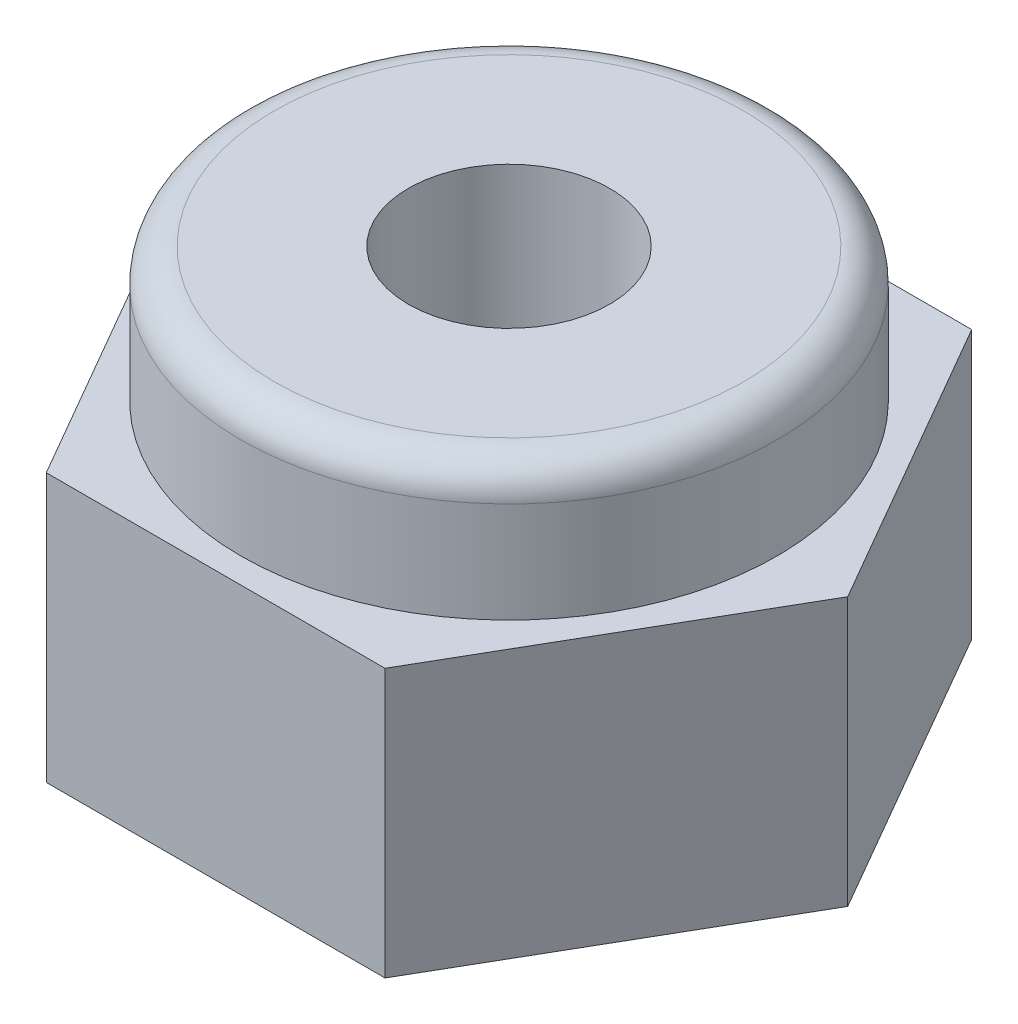
SolidWorks part; units mm, degrees
ref_plane "Front Plane" through (0, 0, 0) normal (0, 0, 1) x (1, 0, 0)
ref_plane "Top Plane" through (0, 0, 0) normal (0, 1, 0) x (1, 0, 0)
ref_plane "Right Plane" through (0, 0, 0) normal (1, 0, 0) x (0, 0, -1)
sketch "Sketch1" plane through (0, 0, 0) normal (0, 1, 0) x (1, 0, 0)
  line L1 (2.5259, 4.375) -> (-2.5259, 4.375)
  line L2 (-2.5259, 4.375) -> (-5.0518, 0)
  line L3 (-5.0518, 0) -> (-2.5259, -4.375)
  line L4 (-2.5259, -4.375) -> (2.5259, -4.375)
  line L5 (2.5259, -4.375) -> (5.0518, 0)
  line L6 (5.0518, 0) -> (2.5259, 4.375)
  circle A0 centre (0, 0) radius 4.375 construction
  circle A1 centre (0, 0) radius 1.5
  dimension "D2" = 3
  dimension "D1" = 8.75
extrude "Boss-Extrude1" add sketch "Sketch1" along normal blind 4
sketch "Sketch2" plane through (0, 4, 0) normal (0, 1, 0) x (1, 0, 0)
  circle A0 centre (0, 0) radius 1.5
  circle A1 centre (0, 0) radius 4
  circle A2 centre (0, 0) radius 1.5 construction
  dimension "D1" = 8
extrude "Boss-Extrude2" add sketch "Sketch2" along normal blind 2
fillet "Fillet1" radius 0.5 1 edges at (0, 6, 4)
